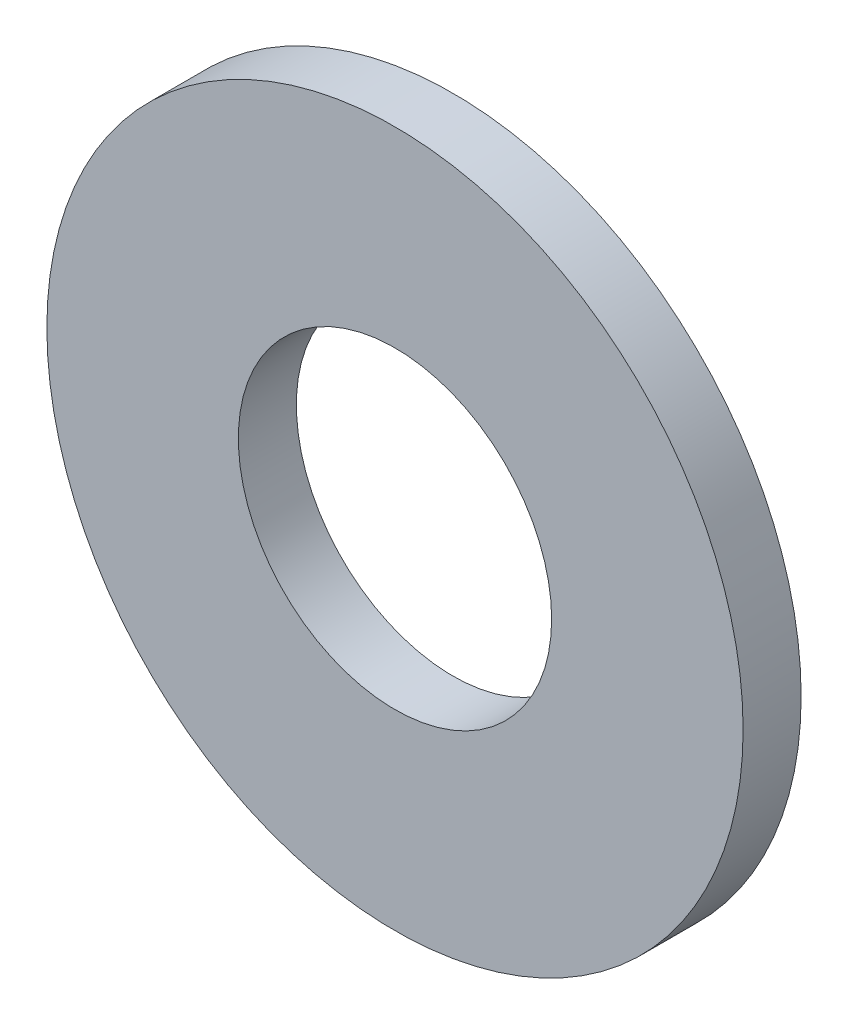
SolidWorks part; units mm, degrees
ref_plane "Face" through (0, 0, 0) normal (0, 0, 1) x (1, 0, 0)
ref_plane "Dessus" through (0, 0, 0) normal (0, 1, 0) x (1, 0, 0)
ref_plane "Droite" through (0, 0, 0) normal (1, 0, 0) x (0, 0, -1)
sketch "Esquisse1" plane through (0, 0, 0) normal (0, 1, 0) x (1, 0, 0)
  line L0 (3, -0.5) -> (3, 0)
  line L1 (3, 0) -> (1.35, 0)
  line L2 (1.35, 0) -> (1.35, -0.5)
  line L3 (1.35, -0.5) -> (3, -0.5)
  line L4 (0, 0) -> (0, -0.5) construction
  dimension "D1" = 1.35
  dimension "D2" = 3
  dimension "D3" = 0.5
revolve "Révolution1" add sketch "Esquisse1" angle 360 about L4
